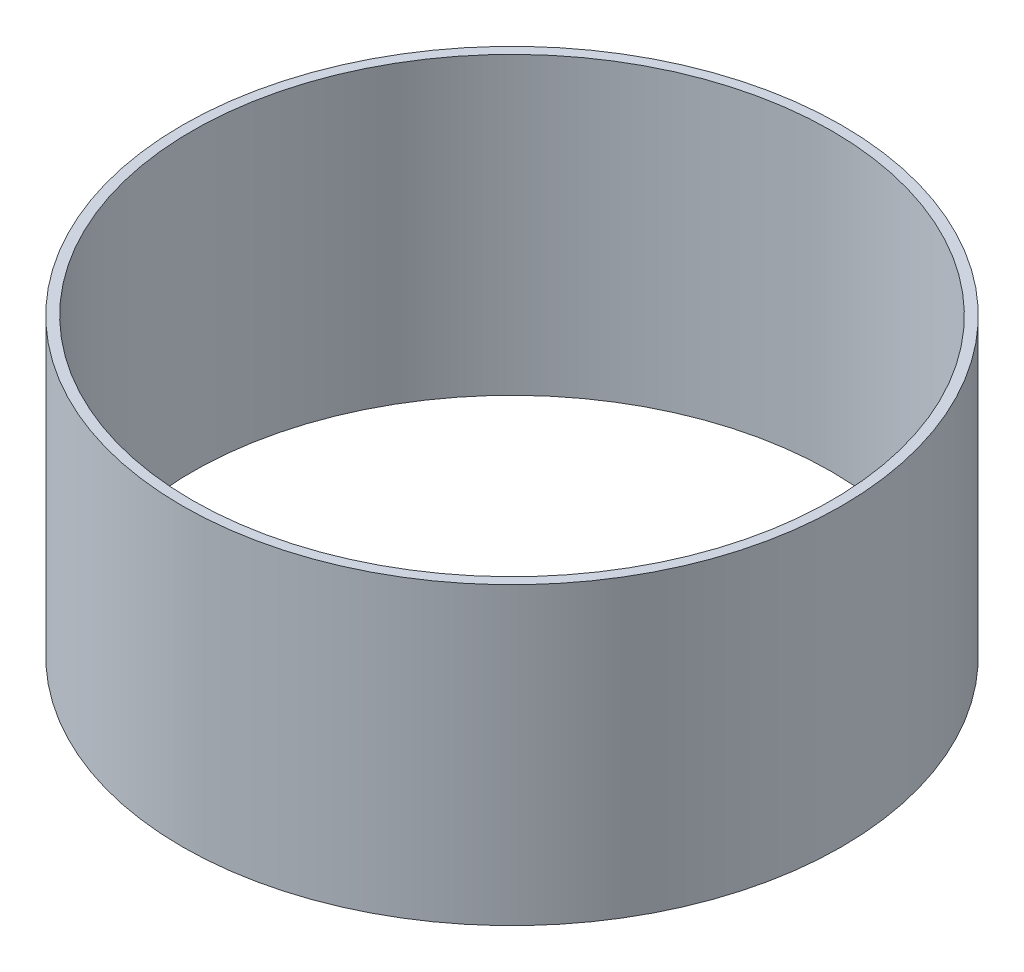
SolidWorks part; units mm, degrees
ref_plane "Front Plane" through (0, 0, 0) normal (0, 0, 1) x (1, 0, 0)
ref_plane "Top Plane" through (0, 0, 0) normal (0, 1, 0) x (1, 0, 0)
ref_plane "Right Plane" through (0, 0, 0) normal (1, 0, 0) x (0, 0, -1)
sketch "Sketch1" plane through (0, 0, 0) normal (0, 1, 0) x (1, 0, 0)
  circle A0 centre (0, 0) radius 32.5
  circle A2 centre (0, 0) radius 33.5
  dimension "D1" = 65
  dimension "D2" = 1
extrude "Boss-Extrude1" add sketch "Sketch1" along normal blind 30
